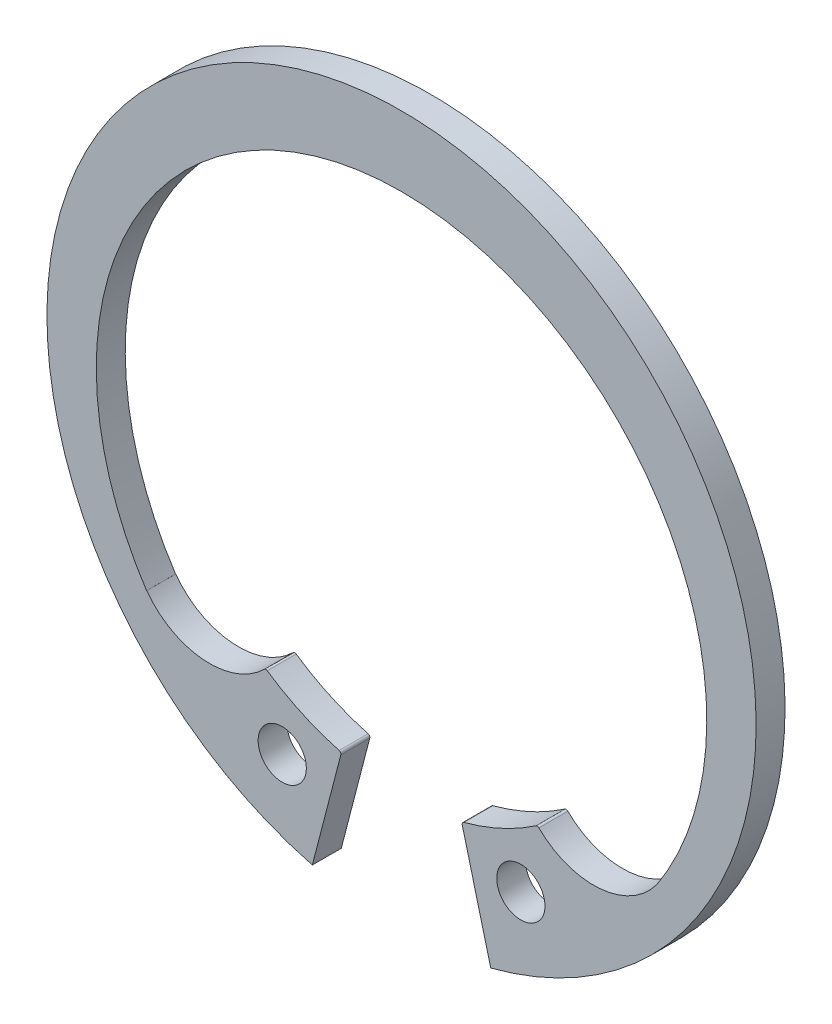
SolidWorks part; units mm, degrees
extrude "Body" add sketch "BodySke" against normal blind 1.2
sketch "BodySke" plane through (0, 0, 0) normal (0, 0, 1) x (1, 0, 0)
  line L0 (-1.5431, 0) -> (1.5431, 0) construction
  line L1 (0, 0) -> (0, 11.8) construction
  line L2 (3.6983, -14.2272) -> (2.9619, -11.3942)
  line L3 (-3.6983, -14.2272) -> (-2.9619, -11.3942)
  line L4 (0, 0) -> (10.306, -10.4822) construction
  line L5 (0, 0) -> (-10.306, -10.4822) construction
  line L6 (-4.6944, -9.9106) -> (-5.1975, -11.8463) construction
  line L7 (4.7571, -10.152) -> (5.1348, -11.6049) construction
  arc A0 (-2.9619, -11.3942) -> (-6.3981, -9.4314) centre (-4.946, -10.8784) ccw
  arc A1 (6.3981, -9.4314) -> (2.9619, -11.3942) centre (4.946, -10.8784) ccw
  arc A2 (9.2894, -9.4482) -> (-9.2894, -9.4482) centre (0, -0.8547) ccw construction
  arc A3 (3.6983, -14.2272) -> (-3.6983, -14.2272) centre (0, 0) ccw
  circle A4 centre (4.946, -10.8784) radius 1
  circle A5 centre (-4.946, -10.8784) radius 1
  circle A6 centre (4.946, -10.8784) radius 2.05 construction
  arc A7 (9.3678, -9.3627) -> (-9.3678, -9.3627) centre (0, -0.8547) ccw
  arc A8 (-4.946, -10.8784) -> (4.946, -10.8784) centre (0, 0) ccw construction
  arc A9 (-9.3678, -9.3627) -> (-6.3981, -9.4314) centre (-7.8503, -7.9845) ccw
  arc A10 (6.3981, -9.4314) -> (9.3678, -9.3627) centre (7.8503, -7.9845) ccw
  dimension "HoleDia" = 2
  dimension "HoleOffsetRad" = 11.95
  dimension "GrooveDia" = 29.4
  dimension "TipRad" = 2.05
  dimension "FilletRad" = 2.05
  dimension "LargeRad" = 11.8
  dimension "SmallRad" = 13.25
  dimension "SmallAngle" = 89.029
  dimension "GapAngle" = 29.143
ref_plane "Plane1" through (0, 0, 0) normal (0, 0, 1) x (1, 0, 0)
ref_plane "Plane2" through (0, 0, 0) normal (0, 1, 0) x (1, 0, 0)
ref_plane "Plane3" through (0, 0, 0) normal (1, 0, 0) x (0, 0, -1)
other "Configuration Table"
sketch "Clipboard" plane through (0, 0, 0) normal (0, 0, 1) x (1, 0, 0)
  line L0 (0, 0) -> (2.9, 0)
  line L1 (0, 0) -> (0, 1.45)
  line L2 (0, 0) -> (0, -4.8)
  circle A0 centre (0, 0) radius 1
  circle A1 centre (0, 0) radius 14
  dimension "HoleDia" = 2
  dimension "BoreDia" = 28
  dimension "LargeSection" = 2.9
  dimension "SmallSection" = 1.45
  dimension "LugSection" = 4.8
sketch "ModLugSke" plane through (0, 0, 0) normal (0, 0, 1) x (1, 0, 0)
  line L0 (3.6983, -14.2272) -> (2.5157, -9.6779)
  line L1 (-3.6983, -14.2272) -> (-2.5157, -9.6779)
  line L2 (7.9601, -5.8862) -> (11.8195, -8.74) construction
  line L3 (-7.9601, -5.8862) -> (-11.8195, -8.74) construction
  line L4 (-3.6983, -14.2272) -> (-2.9619, -11.3942) construction
  line L5 (2.9619, -11.3942) -> (3.6983, -14.2272) construction
  line L6 (0, 0) -> (0, -18.0732) construction
  line L7 (10.5634, -7.8112) -> (11.8195, -8.74)
  line L8 (-11.8195, -8.74) -> (-10.5634, -7.8112)
  arc A0 (3.6983, -14.2272) -> (11.8195, -8.74) centre (0, 0) ccw
  arc A1 (-5.5669, -8.1866) -> (-2.5864, -9.5562) centre (0, 0) ccw
  arc A2 (3.6983, -14.2272) -> (-3.6983, -14.2272) centre (0, 0) ccw construction
  arc A3 (6.3981, -9.4314) -> (2.9619, -11.3942) centre (4.946, -10.8784) ccw construction
  arc A4 (-5.5669, -8.1866) -> (-5.6931, -8.1979) centre (-5.6231, -8.2693) ccw
  arc A5 (-10.5634, -7.8112) -> (-5.6931, -8.1979) centre (-7.9601, -5.8862) ccw
  arc A6 (9.3678, -9.3627) -> (-9.3678, -9.3627) centre (0, -0.8547) ccw construction
  arc A7 (5.6931, -8.1979) -> (10.5634, -7.8112) centre (7.9601, -5.8862) ccw
  arc A8 (2.5864, -9.5562) -> (5.5669, -8.1866) centre (0, 0) ccw
  arc A9 (-11.8195, -8.74) -> (-3.6983, -14.2272) centre (0, 0) ccw
  circle A10 centre (-4.946, -10.8784) radius 1
  circle A11 centre (-4.946, -10.8784) radius 1 construction
  circle A12 centre (4.946, -10.8784) radius 1
  circle A13 centre (4.946, -10.8784) radius 1 construction
  arc A14 (-2.5864, -9.5562) -> (-2.5157, -9.6779) centre (-2.6125, -9.6527) cw
  arc A15 (2.5864, -9.5562) -> (2.5157, -9.6779) centre (2.6125, -9.6527) ccw
  arc A16 (5.5669, -8.1866) -> (5.6931, -8.1979) centre (5.6231, -8.2693) cw
  point P43 (2.4907, -9.5816)
  dimension "D1" = 0.1
extrude "ModLug" add sketch "ModLugSke" against normal through all
sketch "UnlSke" [suppressed] plane through (0, 0, 0) normal (0, 0, 1) x (1, 0, 0)
  line L0 (2.1178, -8.3352) -> (3.2259, -12.6966)
  line L1 (-2.1178, -8.3352) -> (-3.2259, -12.6966)
  line L2 (-3.2259, -12.6966) -> (-2.1422, -8.4315) construction
  line L3 (2.1422, -8.4315) -> (3.2259, -12.6966) construction
  arc A0 (2.1178, -8.3352) -> (-2.1178, -8.3352) centre (0, 0) ccw
  arc A1 (3.2259, -12.6966) -> (-3.2259, -12.6966) centre (0, 0) ccw
  arc A2 (3.2259, -12.6966) -> (-3.2259, -12.6966) centre (0, 0) ccw construction
  circle A4 centre (-4.4431, -9.5688) radius 1
  circle A5 centre (4.4431, -9.5688) radius 1
  circle A6 centre (4.4431, -9.5688) radius 1 construction
  circle A7 centre (-4.4431, -9.5688) radius 1 construction
  arc A8 (2.2134, -8.3103) -> (4.9183, -7.0548) centre (0, 0) ccw construction
extrude "Unlug" [suppressed] add sketch "UnlSke" against normal through all
equation "' \"BoreDia@Clipboard\" = 8"
equation "' \"Thickness@Body\" = 0.8"
equation "' \"GrooveDia@BodySke\" = 8.4"
equation "' \"LugSection@Clipboard\" = 2.4"
equation "' \"LargeSection@Clipboard\" = 1.1"
equation "' \"HoleDia@Clipboard\" = 1.0"
equation "' \"BoreDia@Clipboard\" = 25"
equation "' \"Thickness@Body\" = 1.2"
equation "' \"GrooveDia@BodySke\" = 26.2"
equation "' \"LugSection@Clipboard\" = 4.5"
equation "' \"LargeSection@Clipboard\" = 2.7"
equation "' \"HoleDia@Clipboard\" = 2"
equation "\"SmallSection@Clipboard\" = \"LargeSection@Clipboard\" * 0.5"
equation "\"TipRad@BodySke\" = (\"LugSection@Clipboard\" - (\"GrooveDia@BodySke\" / 2  -  \"BoreDia@Clipboard\" / 2 ) ) / 2"
equation "\"HoleOffsetRad@BodySke\" = (\"GrooveDia@BodySke\" / 2) - \"LugSection@Clipboard\"  + \"TipRad@BodySke\""
equation "\"LargeRad@BodySke\" =  \"GrooveDia@BodySke\" / 2 -  \"LargeSection@Clipboard\""
equation "\"SmallRad@BodySke\" =  \"GrooveDia@BodySke\" / 2 -  \"SmallSection@Clipboard\""
equation "\"HoleDia@BodySke\" =  \"HoleDia@Clipboard\""
equation "\"FilletRad@BodySke\" = \"TipRad@BodySke\" * 1.0"
equation "\"GapAngle@BodySke\" = 360 - 0.965 * 360 * ( \"BoreDia@Clipboard\" /  \"GrooveDia@BodySke\")"
equation "\"LugAng@ModLugSke\" = \"GapAngle@BodySke\"  + 2 * 360 * (\"LugSection@Clipboard\" / (\"BoreDia@Clipboard\" * 3.1416))"
